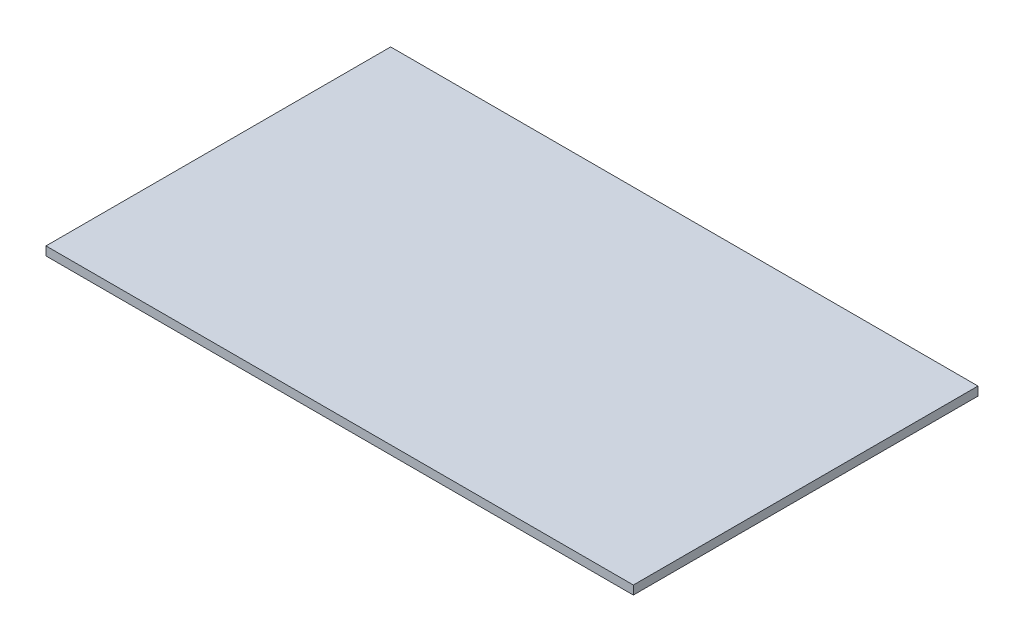
SolidWorks part; units mm, degrees
ref_plane "Front Plane" through (0, 0, 0) normal (0, 0, 1) x (1, 0, 0)
ref_plane "Top Plane" through (0, 0, 0) normal (0, 1, 0) x (1, 0, 0)
ref_plane "Right Plane" through (0, 0, 0) normal (1, 0, 0) x (0, 0, -1)
sketch "Esquisse1" plane through (0, 0, 0) normal (0, 1, 0) x (1, 0, 0)
  line L1 (-605, 355) -> (605, 355)
  line L2 (-605, 355) -> (-605, -355)
  line L3 (-605, -355) -> (605, -355)
  line L4 (605, 355) -> (605, -355)
  line L5 (-605, 355) -> (605, -355) construction
  line L6 (-605, -355) -> (605, 355) construction
  point P0 (0, 0)
extrude "Boss.-Extru.1" add sketch "Esquisse1" along normal blind 18 contours L2 L3 L4 L1
